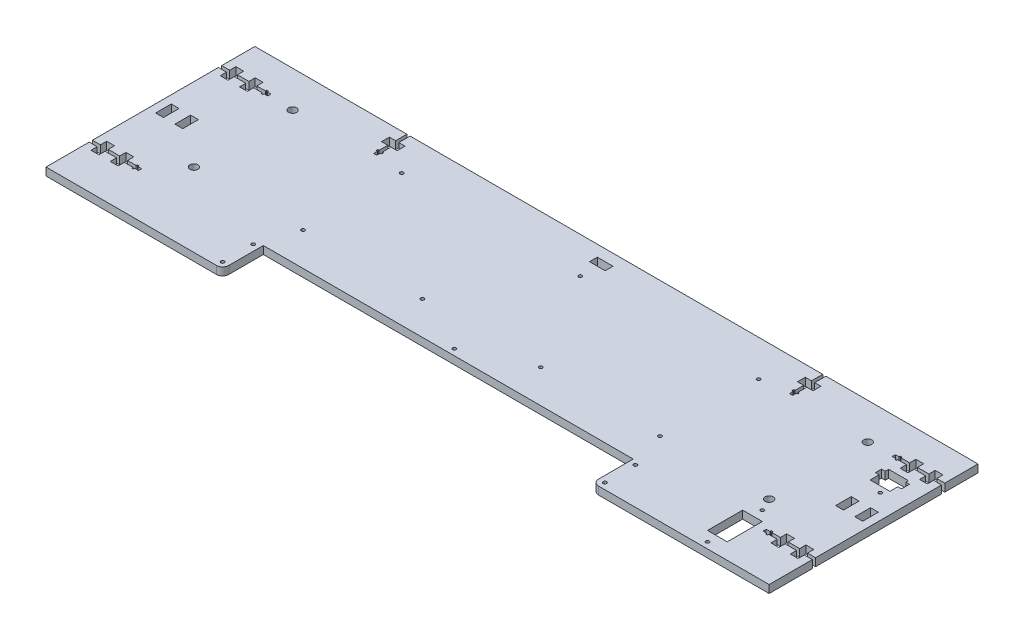
SolidWorks part; units mm, degrees
ref_plane "Front Plane" through (0, 0, 0) normal (0, 0, 1) x (1, 0, 0)
ref_plane "Top Plane" through (0, 0, 0) normal (0, 1, 0) x (1, 0, 0)
ref_plane "Right Plane" through (0, 0, 0) normal (1, 0, 0) x (0, 0, -1)
sketch "Sketch1" plane through (0, 0, 0) normal (0, 1, 0) x (1, 0, 0)
  line L1 (304.8, -152.4) -> (-304.8, -152.4)
  line L2 (304.8, -152.4) -> (304.8, 152.4)
  line L3 (304.8, 152.4) -> (-304.8, 152.4)
  line L4 (-304.8, -152.4) -> (-304.8, 152.4)
  line L5 (304.8, -152.4) -> (-304.8, 152.4) construction
  line L6 (304.8, 152.4) -> (-304.8, -152.4) construction
  point P0 (0, 0)
  dimension "D1" = 304.8
  dimension "D2" = 609.6
extrude "MDFstock" add sketch "Sketch1" along normal blind 6.35
sketch "Sketch2" plane through (0, 0, 0) normal (0, 1, 0) x (1, 0, 0)
  line L0 (-144.75, -92.4) -> (-48, -92.4) construction
  line L1 (-48, -92.4) -> (48, -92.4) construction
  line L2 (48, -92.4) -> (144.75, -92.4) construction
  line L4 (-150, -142.4) -> (150, -142.4) construction
  line L5 (-150, -142.4) -> (-150, -119.4) construction
  line L6 (-150, -119.4) -> (150, -119.4) construction
  line L7 (150, -142.4) -> (150, -119.4) construction
  line L8 (-304.8, -152.4) -> (304.8, -152.4) construction
  line L9 (-150, -119.4) -> (150, -119.4)
  line L10 (-150, -119.4) -> (-150, -152.4)
  line L11 (-150, -152.4) -> (150, -152.4)
  line L12 (150, -119.4) -> (150, -152.4)
  circle A0 centre (-144.75, -92.4) radius 1.4
  circle A1 centre (-48, -92.4) radius 1.4
  circle A2 centre (48, -92.4) radius 1.4
  circle A3 centre (144.75, -92.4) radius 1.4
  circle A4 centre (-144.75, -12.4) radius 1.4
  circle A5 centre (0, -12.4) radius 1.4
  circle A6 centre (144.75, -12.4) radius 1.4
  circle A7 centre (-155, -122.65) radius 1.4
  circle A8 centre (-155, -147.4) radius 1.4
  circle A9 centre (155, -122.65) radius 1.4
  circle A10 centre (155, -147.4) radius 1.4
  circle A11 centre (0, -114.4) radius 1.4
  point P14 (0, -92.4)
  point P26 (0, -119.4)
  dimension "D1" = 2.8
  dimension "D3" = 289.5
  dimension "D8" = 300
  dimension "D2" = 80
  dimension "D4" = 107
  dimension "D5" = 23
  dimension "D6" = 10
  dimension "D7" = 96
  dimension "D9" = 5
  dimension "D10" = 5
  dimension "D11" = 5
  dimension "D12" = 3.25
  dimension "D13" = 5
extrude "bedVergeHoles" cut sketch "Sketch2" along normal through all
fillet "Fillet1" radius 5 2 edges at (150, 3.175, 152.4) (-150, 3.175, 152.4)
sketch "Sketch3" plane through (0, 6.35, 0) normal (0, 1, 0) x (1, 0, 0)
  line L0 (-264.75, -109.7) -> (-271.1, -109.7)
  line L1 (-264.75, -109.7) -> (-264.75, -122.4)
  line L2 (-271.1, -109.7) -> (-271.1, -122.4)
  line L3 (-264.75, -122.4) -> (-271.1, -122.4)
  line L4 (-253.25, -114.75) -> (-253.25, -117.35)
  line L5 (-280.4, -109.7) -> (-286.75, -109.7)
  line L6 (-280.4, -109.7) -> (-280.4, -122.4)
  line L7 (-286.75, -109.7) -> (-286.75, -122.4)
  line L8 (-280.4, -122.4) -> (-286.75, -122.4)
  line L9 (-280.4, -57.3) -> (-286.75, -57.3)
  line L10 (-280.4, -57.3) -> (-280.4, -70)
  line L11 (-286.75, -57.3) -> (-286.75, -70)
  line L12 (-280.4, -70) -> (-286.75, -70)
  line L13 (150, -119.4) -> (-150, -119.4) construction
  line L14 (-280.4, -4.9) -> (-286.75, -4.9)
  line L15 (-280.4, -4.9) -> (-280.4, -17.6)
  line L16 (-286.75, -4.9) -> (-286.75, -17.6)
  line L17 (-280.4, -17.6) -> (-286.75, -17.6)
  line L18 (-264.75, -57.3) -> (-271.1, -57.3)
  line L19 (-264.75, -57.3) -> (-264.75, -70)
  line L20 (-271.1, -57.3) -> (-271.1, -70)
  line L21 (-264.75, -70) -> (-271.1, -70)
  line L22 (-264.75, -4.9) -> (-271.1, -4.9)
  line L23 (-264.75, -4.9) -> (-264.75, -17.6)
  line L24 (-271.1, -4.9) -> (-271.1, -17.6)
  line L25 (-264.75, -17.6) -> (-271.1, -17.6)
  line L26 (0, 0) -> (0, -119.4) construction
  line L27 (264.75, -17.6) -> (271.1, -17.6)
  line L28 (271.1, -4.9) -> (271.1, -17.6)
  line L29 (264.75, -4.9) -> (264.75, -17.6)
  line L30 (264.75, -4.9) -> (271.1, -4.9)
  line L31 (264.75, -70) -> (271.1, -70)
  line L32 (271.1, -57.3) -> (271.1, -70)
  line L33 (264.75, -57.3) -> (264.75, -70)
  line L34 (264.75, -57.3) -> (271.1, -57.3)
  line L35 (280.4, -17.6) -> (286.75, -17.6)
  line L36 (286.75, -4.9) -> (286.75, -17.6)
  line L37 (280.4, -4.9) -> (280.4, -17.6)
  line L38 (280.4, -4.9) -> (286.75, -4.9)
  line L39 (280.4, -70) -> (286.75, -70)
  line L40 (286.75, -57.3) -> (286.75, -70)
  line L41 (280.4, -57.3) -> (280.4, -70)
  line L42 (280.4, -57.3) -> (286.75, -57.3)
  line L43 (280.4, -122.4) -> (286.75, -122.4)
  line L44 (286.75, -109.7) -> (286.75, -122.4)
  line L45 (280.4, -109.7) -> (280.4, -122.4)
  line L46 (280.4, -109.7) -> (286.75, -109.7)
  line L47 (264.75, -122.4) -> (271.1, -122.4)
  line L48 (271.1, -109.7) -> (271.1, -122.4)
  line L49 (264.75, -109.7) -> (264.75, -122.4)
  line L50 (264.75, -109.7) -> (271.1, -109.7)
  line L51 (253.25, -9.95) -> (293.25, -9.95)
  line L52 (256.25, -113.75) -> (257.75, -113.75)
  line L53 (256.25, -113.75) -> (256.25, -118.35)
  line L54 (256.25, -118.35) -> (257.75, -118.35)
  line L55 (257.75, -113.75) -> (257.75, -118.35)
  line L56 (256.25, -8.95) -> (257.75, -8.95)
  line L57 (256.25, -8.95) -> (256.25, -13.55)
  line L58 (256.25, -13.55) -> (257.75, -13.55)
  line L59 (257.75, -8.95) -> (257.75, -13.55)
  line L60 (253.25, -114.75) -> (293.25, -114.75)
  line L61 (253.25, -114.75) -> (253.25, -117.35)
  line L62 (253.25, -117.35) -> (293.25, -117.35)
  line L63 (293.25, -114.75) -> (293.25, -117.35)
  line L64 (253.25, -9.95) -> (253.25, -12.55)
  line L65 (253.25, -12.55) -> (293.25, -12.55)
  line L66 (293.25, -9.95) -> (293.25, -12.55)
  line L67 (293.25, -152.4) -> (304.8, -152.4)
  line L68 (293.25, -152.4) -> (293.25, 152.4)
  line L69 (293.25, 152.4) -> (304.8, 152.4)
  line L70 (304.8, -152.4) -> (304.8, 152.4)
  line L71 (-257.75, -113.75) -> (-257.75, -118.35)
  line L72 (-256.25, -118.35) -> (-257.75, -118.35)
  line L73 (-256.25, -113.75) -> (-256.25, -118.35)
  line L74 (-256.25, -113.75) -> (-257.75, -113.75)
  line L75 (-253.25, -9.95) -> (-253.25, -12.55)
  line L76 (-257.75, -8.95) -> (-257.75, -13.55)
  line L77 (-256.25, -13.55) -> (-257.75, -13.55)
  line L78 (-256.25, -8.95) -> (-256.25, -13.55)
  line L79 (-256.25, -8.95) -> (-257.75, -8.95)
  line L80 (-304.8, -152.4) -> (-304.8, 152.4)
  line L81 (-293.25, 152.4) -> (-304.8, 152.4)
  line L82 (-293.25, -152.4) -> (-293.25, 152.4)
  line L83 (-293.25, -152.4) -> (-304.8, -152.4)
  line L84 (-293.25, -9.95) -> (-293.25, -12.55)
  line L85 (-253.25, -12.55) -> (-293.25, -12.55)
  line L86 (-293.25, -114.75) -> (-293.25, -117.35)
  line L87 (-253.25, -117.35) -> (-293.25, -117.35)
  line L88 (-253.25, -114.75) -> (-293.25, -114.75)
  line L89 (-253.25, -9.95) -> (-293.25, -9.95)
  circle A0 centre (-144.75, -92.4) radius 1.4 construction
  point P63 (264.75, -11.25)
  point P64 (257.75, -11.25)
  point P65 (257.75, -116.05)
  point P66 (264.75, -116.05)
  point P71 (253.25, -116.05)
  point P76 (253.25, -11.25)
  point P89 (-253.25, -116.05)
  point P90 (-257.75, -116.05)
  point P97 (-253.25, -11.25)
  point P98 (-257.75, -11.25)
  line M10 (-304.8, -152.4) -> (-155, -152.4)
  line M14 (155, -152.4) -> (304.8, -152.4)
  line M15 (304.8, -152.4) -> (304.8, 152.4)
  line M16 (304.8, 152.4) -> (-304.8, 152.4)
  line M17 (-304.8, 152.4) -> (-304.8, -152.4)
  dimension "D8" = 120
  dimension "D1" = 3
  dimension "D2" = 2
  dimension "D3" = 3
  dimension "D4" = 6.35
  dimension "D5" = 12.7
  dimension "D6" = 117.5
  dimension "D7" = 22
  dimension "D9" = 4.6
  dimension "D10" = 1.5
  dimension "D11" = 2.6
  dimension "D12" = 40
  dimension "D13" = 7
  dimension "D14" = 3
extrude "sidingHoles" cut sketch "Sketch3" against normal through all contours L82 M10 M16 M17 | L68 L66 L63 M14 M15 M16 | L85 L84 L89 L75 | L16 L17 L15 L14 | L25 L24 L22 L23 | L77 L76 L79 L78 | L12 L11 L9 L10 | L20 L21 L19 L18 | L8 L7 L5 L6 | L87 L86 L88 L4 | L3 L2 L0 L1 | L72 L71 L74 L73 | L36 L35 L37 L38 | L28 L27 L29 L30 | L58 L59 L56 L57 | L31 L32 L34 L33 | L39 L40 L42 L41 | L54 L55 L52 L53 | L47 L48 L50 L49 | L43 L44 L46 L45
sketch "Sketch5" plane through (0, 6.35, 0) normal (0, 1, 0) x (1, 0, 0)
  line L0 (-264.75, -4.9) -> (-271.1, -4.9) construction
  line L1 (-175, 7.85) -> (-162.3, 7.85)
  line L2 (-175, 7.85) -> (-175, 1.5)
  line L3 (-175, 1.5) -> (-162.3, 1.5)
  line L4 (-162.3, 7.85) -> (-162.3, 1.5)
  line L5 (-6.35, 7.85) -> (6.35, 7.85)
  line L6 (-6.35, 7.85) -> (-6.35, 1.5)
  line L7 (-6.35, 1.5) -> (6.35, 1.5)
  line L8 (6.35, 7.85) -> (6.35, 1.5)
  line L9 (162.3, 7.85) -> (175, 7.85)
  line L10 (162.3, 7.85) -> (162.3, 1.5)
  line L11 (162.3, 1.5) -> (175, 1.5)
  line L12 (175, 7.85) -> (175, 1.5)
  line L13 (-264.75, -57.3) -> (-271.1, -57.3) construction
  line L14 (-264.75, -57.3) -> (-264.75, -70) construction
  line L15 (-162.3, 7.85) -> (-6.35, 7.85) construction
  line L16 (6.35, 7.85) -> (162.3, 7.85) construction
  line L17 (-253.25, -9.95) -> (-253.25, -12.55) construction
  line L18 (-167.35, 17) -> (-169.95, 17)
  line L19 (-167.35, 17) -> (-167.35, -10)
  line L20 (-167.35, -10) -> (-169.95, -10)
  line L21 (-169.95, 17) -> (-169.95, -10)
  line L22 (167.35, 17) -> (169.95, 17)
  line L23 (167.35, 17) -> (167.35, -10)
  line L24 (167.35, -10) -> (169.95, -10)
  line L25 (169.95, 17) -> (169.95, -10)
  line L26 (-170.95, -5.5) -> (-166.35, -5.5)
  line L27 (-170.95, -5.5) -> (-170.95, -7)
  line L28 (-170.95, -7) -> (-166.35, -7)
  line L29 (-166.35, -5.5) -> (-166.35, -7)
  line L30 (166.35, -5.5) -> (170.95, -5.5)
  line L31 (166.35, -5.5) -> (166.35, -7)
  line L32 (166.35, -7) -> (170.95, -7)
  line L33 (170.95, -5.5) -> (170.95, -7)
  line L34 (-256.25, -13.55) -> (-257.75, -13.55) construction
  line L35 (293.25, -9.95) -> (293.25, 152.4) construction
  line L36 (293.25, 17) -> (-293.25, 17)
  line L37 (293.25, 17) -> (293.25, 152.4)
  line L38 (293.25, 152.4) -> (-293.25, 152.4)
  line L39 (-293.25, 17) -> (-293.25, 152.4)
  point P14 (0, 7.85)
  point P41 (-168.65, 1.5)
  point P42 (-168.65, -10)
  point P43 (-168.65, -5.5)
  point P44 (168.65, -5.5)
  point P45 (168.65, -10)
  point P46 (168.65, 1.5)
  dimension "D1" = 6.4
  dimension "D2" = 350
  dimension "D3" = 4.6
  dimension "D4" = 27
  dimension "D5" = 7
  dimension "D6" = 3
extrude "backingHoles" cut sketch "Sketch5" against normal through all contours L39 L36 L18 L22 L37 L38 | L3 L4 L1 L2 | L28 L29 L26 L27 | L7 L8 L5 L6 | L11 L12 L9 L10 | L32 L33 L30 L31
sketch "Sketch6" plane through (0, 6.35, 0) normal (0, 1, 0) x (1, 0, 0)
  line L0 (0, 0) -> (0, -169.224) construction
  line L1 (-293.25, -152.4) -> (-155, -152.4) construction
  line L2 (-293.25, -114.75) -> (-293.25, -12.55) construction
  circle A0 centre (-233.25, -92.4) radius 3.25
  circle A1 centre (-233.25, -12.4) radius 3.25
  circle A2 centre (233.25, -92.4) radius 3.25
  circle A3 centre (233.25, -12.4) radius 3.25
  dimension "D1" = 6.5
  dimension "D3" = 80
  dimension "D2" = 60
  dimension "D4" = 60
extrude "legHoles" cut sketch "Sketch6" against normal through all
sketch "Sketch7" plane through (0, 6.35, 0) normal (0, 1, 0) x (1, 0, 0)
  line L0 (293.25, -114.75) -> (293.25, -12.55) construction
  line L1 (260.75, -23) -> (276.75, -23)
  line L2 (260.75, -23) -> (260.75, -33.5)
  line L3 (260.75, -33.5) -> (276.75, -33.5)
  line L4 (276.75, -23) -> (276.75, -33.5)
  line L5 (276.75, -25) -> (279.75, -25)
  line L6 (276.75, -25) -> (276.75, -31.5)
  line L7 (276.75, -31.5) -> (279.75, -31.5)
  line L8 (279.75, -25) -> (279.75, -31.5)
  line L9 (293.25, 17) -> (169.95, 17) construction
  line L11 (271.1, -33.5) -> (276.75, -33.5)
  line L12 (271.1, -33.5) -> (271.1, -38)
  line L13 (271.1, -38) -> (276.75, -38)
  line L14 (276.75, -33.5) -> (276.75, -38)
  line L15 (271.1, -12.55) -> (271.1, -17.6) construction
  line L16 (257.75, -25.75) -> (260.75, -25.75)
  line L17 (260.75, -33.5) -> (271.1, -33.5)
  line L18 (260.75, -33.5) -> (260.75, -38)
  line L19 (260.75, -38) -> (271.1, -38)
  line L20 (271.1, -33.5) -> (271.1, -38)
  line L21 (257.75, -25.75) -> (257.75, -30.75)
  line L22 (257.75, -30.75) -> (260.75, -30.75)
  line L23 (260.75, -25.75) -> (260.75, -30.75)
  circle A0 centre (273.925, -42.9) radius 1.4
  point P8 (276.75, -28.25)
  point P20 (273.925, -38)
  point P26 (260.75, -28.25)
  dimension "D8" = 2.8
  dimension "D1" = 16
  dimension "D2" = 10.5
  dimension "D3" = 3
  dimension "D4" = 6.5
  dimension "D5" = 16.5
  dimension "D6" = 40
  dimension "D7" = 4.5
  dimension "D9" = 4.9
  dimension "D10" = 5
  dimension "D11" = 3
extrude "limitSwitchHole" cut sketch "Sketch7" against normal through all contours L18 L19 L12 L3 | L14 L3 L12 L13 | L4 L1 L2 L3 | L8 L5 L4 L7 | L21 L22 L2 L16 | A0
sketch "Sketch8" plane through (0, 6.35, 0) normal (0, 1, 0) x (1, 0, 0)
  line L0 (246.25, -110.9) -> (230.25, -139.4) construction
  line L1 (230.25, -110.9) -> (246.25, -110.9)
  line L2 (230.25, -110.9) -> (230.25, -139.4)
  line L3 (230.25, -139.4) -> (246.25, -139.4)
  line L4 (246.25, -110.9) -> (246.25, -139.4)
  line L5 (155, -152.4) -> (293.25, -152.4) construction
  line L7 (293.25, -152.4) -> (293.25, -117.35) construction
  circle A0 centre (238.25, -125.15) radius 6 construction
  circle A1 centre (238.25, -102.9) radius 1.4
  circle A2 centre (238.25, -147.4) radius 1.4
  point P0 (238.25, -125.15)
  dimension "D3" = 12
  dimension "D4" = 2.8
  dimension "D1" = 28.5
  dimension "D2" = 16
  dimension "D5" = 8
  dimension "D6" = 8
  dimension "D7" = 55
  dimension "D8" = 5
extrude "EmergencyStop" cut sketch "Sketch8" against normal blind 10 contours A2 | A1 | A0
